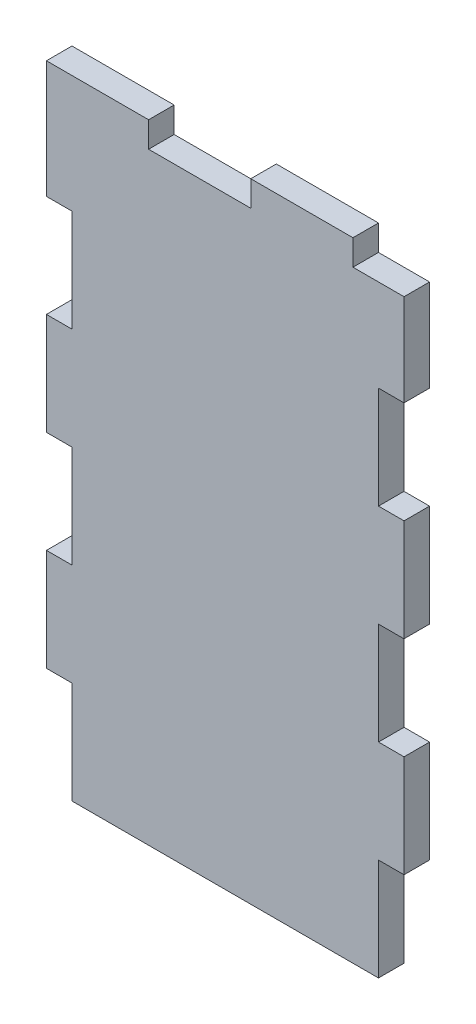
SolidWorks part; units mm, degrees
ref_plane "정면" through (0, 0, 0) normal (0, 0, 1) x (1, 0, 0)
ref_plane "윗면" through (0, 0, 0) normal (0, 1, 0) x (1, 0, 0)
ref_plane "우측면" through (0, 0, 0) normal (1, 0, 0) x (0, 0, -1)
sketch "스케치1" plane through (0, 0, 0) normal (0, 0, 1) x (1, 0, 0)
  line L1 (-35, 59) -> (35, 59)
  line L2 (-35, 59) -> (-35, -59)
  line L3 (-35, -59) -> (35, -59)
  line L4 (35, 59) -> (35, -59)
  line L5 (-35, 59) -> (35, -59) construction
  line L6 (-35, -59) -> (35, 59) construction
  point P0 (0, 0)
  dimension "D1" = 118
  dimension "D2" = 70
extrude "보스-돌출1" add sketch "스케치1" along normal blind 5
sketch "스케치2" plane through (0, 0, 5) normal (0, 0, 1) x (1, 0, 0)
  line L1 (-35, -59) -> (-30, -59)
  line L2 (-35, -59) -> (-35, -39)
  line L3 (-35, -39) -> (-30, -39)
  line L4 (-30, -59) -> (-30, -39)
  dimension "D1" = 5
  dimension "D2" = 20
extrude "컷-돌출1" cut sketch "스케치2" against normal up to next and the other way through all
pattern_linear "선형 패턴1" count 3 spacing 40 along (0, 1, 0) of "컷-돌출1"
sketch "스케치3" plane through (0, 0, 5) normal (0, 0, 1) x (1, 0, 0)
  line L1 (-35, 64) -> (-15, 64)
  line L2 (-35, 64) -> (-35, 59)
  line L3 (-35, 59) -> (-15, 59)
  line L4 (-15, 64) -> (-15, 59)
  point P6 (0, 0)
  dimension "D1" = 5
  dimension "D2" = 20
sketch "스케치4" plane through (0, 0, 5) normal (0, 0, 1) x (1, 0, 0)
  line L1 (30, -59) -> (35, -59)
  line L2 (30, -59) -> (30, -39)
  line L3 (30, -39) -> (35, -39)
  line L4 (35, -59) -> (35, -39)
  dimension "D1" = 5
  dimension "D2" = 20
extrude "컷-돌출3" cut sketch "스케치4" against normal up to next
pattern_linear "선형 패턴4" count 3 spacing 40 along (0, 1, 0) of "컷-돌출3"
extrude "보스-돌출2" add sketch "스케치3" against normal up to surface (5 mm away) up to face at (0, 0.8333, 0)
pattern_linear "선형 패턴5" count 2 spacing 40 along (1, 0, 0) of "보스-돌출2"
